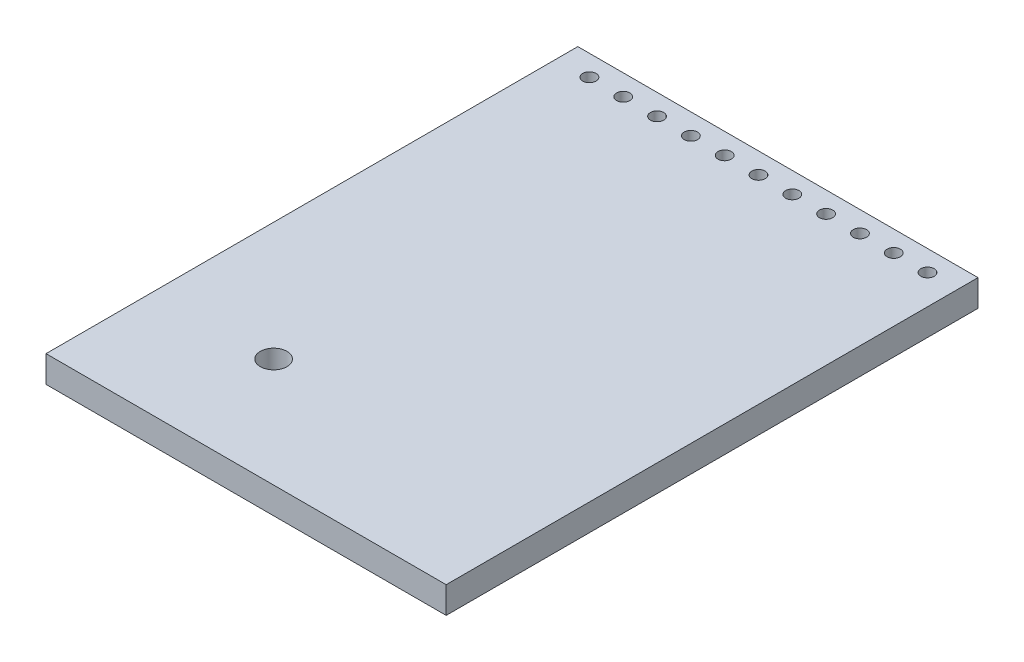
SolidWorks part; units mm, degrees
ref_plane "Front Plane" through (0, 0, 0) normal (0, 0, 1) x (1, 0, 0)
ref_plane "Top Plane" through (0, 0, 0) normal (0, 1, 0) x (1, 0, 0)
ref_plane "Right Plane" through (0, 0, 0) normal (1, 0, 0) x (0, 0, -1)
sketch "Sketch1" plane through (0, 0, 0) normal (0, 0, 1) x (1, 0, 0)
  line L1 (0, 0) -> (30.06, 0)
  line L2 (0, 0) -> (0, 2)
  line L3 (0, 2) -> (30.06, 2)
  line L4 (30.06, 0) -> (30.06, 2)
  dimension "D1" = 30.06
  dimension "D2" = 2
extrude "Boss-Extrude1" add sketch "Sketch1" along normal blind 39.95
sketch "Sketch2" plane through (0, 2, 0) normal (0, 1, 0) x (1, 0, 0)
  line L0 (0, -39.95) -> (0, 0) construction
  line L2 (30.06, -39.95) -> (0, -39.95) construction
  circle A0 centre (8.9, -31.75) radius 1
  dimension "D1" = 2
  dimension "D2" = 8.9
  dimension "D3" = 8.2
extrude "Cut-Extrude1" cut sketch "Sketch2" against normal blind 39.95
sketch "Sketch3" plane through (0, 2, 0) normal (0, 1, 0) x (1, 0, 0)
  line L0 (30.06, -39.95) -> (30.06, 0) construction
  line L1 (30.06, 0) -> (0, 0) construction
  circle A0 centre (27.83, -1.56) radius 0.5
  dimension "D1" = 1
  dimension "D2" = 2.23
  dimension "D3" = 1.56
extrude "Cut-Extrude2" cut sketch "Sketch3" against normal blind 4.5
pattern_linear "LPattern1" count 11 spacing 2.54 along (-1, 0, 0) of "Cut-Extrude2"
sketch "Sketch4" plane through (0, 0, 0) normal (0, -1, 0) x (1, 0, 0)
  line L0 (30.06, 39.95) -> (30.06, 0) construction
  line L1 (14.71, 37.2) -> (13.41, 37.2)
  line L2 (14.71, 37.2) -> (14.71, 35.2)
  line L3 (14.71, 35.2) -> (13.41, 35.2)
  line L4 (13.41, 37.2) -> (13.41, 35.2)
  line L5 (0, 39.95) -> (30.06, 39.95) construction
  dimension "D1" = 15.35
  dimension "D2" = 2.75
  dimension "D3" = 2
  dimension "D4" = 1.3
extrude "Boss-Extrude2" add sketch "Sketch4" along normal blind 0.2
sketch "Sketch5" plane through (0, 0, 0) normal (0, -1, 0) x (1, 0, 0)
  line L1 (4.76, 37.36) -> (3.76, 37.36)
  line L2 (4.76, 37.36) -> (4.76, 36.36)
  line L3 (4.76, 36.36) -> (3.76, 36.36)
  line L4 (3.76, 37.36) -> (3.76, 36.36)
  line L5 (0, 39.95) -> (30.06, 39.95) construction
  line L6 (30.06, 39.95) -> (30.06, 0) construction
  dimension "D1" = 1
  dimension "D2" = 1
  dimension "D3" = 25.3
  dimension "D4" = 2.59
extrude "Boss-Extrude3" add sketch "Sketch5" along normal blind 0.2
